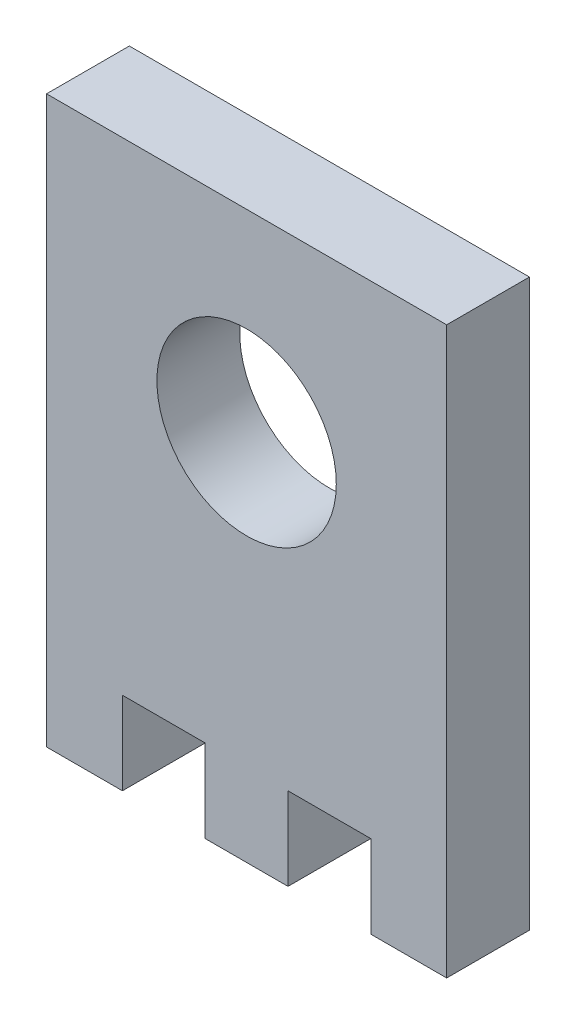
SolidWorks part; units mm, degrees
ref_plane "Front Plane" through (0, 0, 0) normal (0, 0, 1) x (1, 0, 0)
ref_plane "Top Plane" through (0, 0, 0) normal (0, 1, 0) x (1, 0, 0)
ref_plane "Right Plane" through (0, 0, 0) normal (1, 0, 0) x (0, 0, -1)
sketch "Sketch1" plane through (0, 0, 0) normal (0, 0, 1) x (1, 0, 0)
  line L0 (11.4953, 26.2783) -> (11.4953, 5.7829) construction
  line L1 (4.2453, 5.7783) -> (4.2453, 26.2783)
  line L2 (4.2453, 26.2783) -> (18.7453, 26.2783)
  line L3 (18.7453, 5.9692) -> (18.7453, 26.2783)
  line L4 (4.2453, 5.7783) -> (18.7453, 26.2783) construction
  line L5 (4.2453, 26.2783) -> (18.7453, 5.9692) construction
  line L6 (6.9953, 5.7783) -> (6.9953, 8.7783)
  line L7 (6.9953, 8.7783) -> (9.9953, 8.7783)
  line L8 (9.9953, 5.7783) -> (9.9953, 8.7783)
  line L9 (15.9953, 8.7783) -> (12.9953, 8.7783)
  line L10 (12.9953, 5.7783) -> (12.9953, 8.7783)
  line L11 (15.9953, 5.7783) -> (15.9953, 8.7783)
  line L16 (18.7453, 5.9692) -> (18.7453, 5.7783)
  line L17 (4.2453, 5.7783) -> (6.9953, 5.7783)
  line L18 (15.9953, 5.7783) -> (18.7453, 5.7783)
  line L19 (9.9953, 5.7783) -> (12.9953, 5.7783)
  circle A0 centre (11.4953, 19.2783) radius 3.25
  point P0 (11.5292, 16.0762)
  dimension "D10" = 6.5
  dimension "D1" = 20.5
  dimension "D2" = 3
  dimension "D3" = 3
  dimension "D4" = 1.5
  dimension "D5" = 3
  dimension "D7" = 14.5
  dimension "D8" = 0
  dimension "D9" = 7
extrude "Boss-Extrude1" add sketch "Sketch1" along normal blind 3
